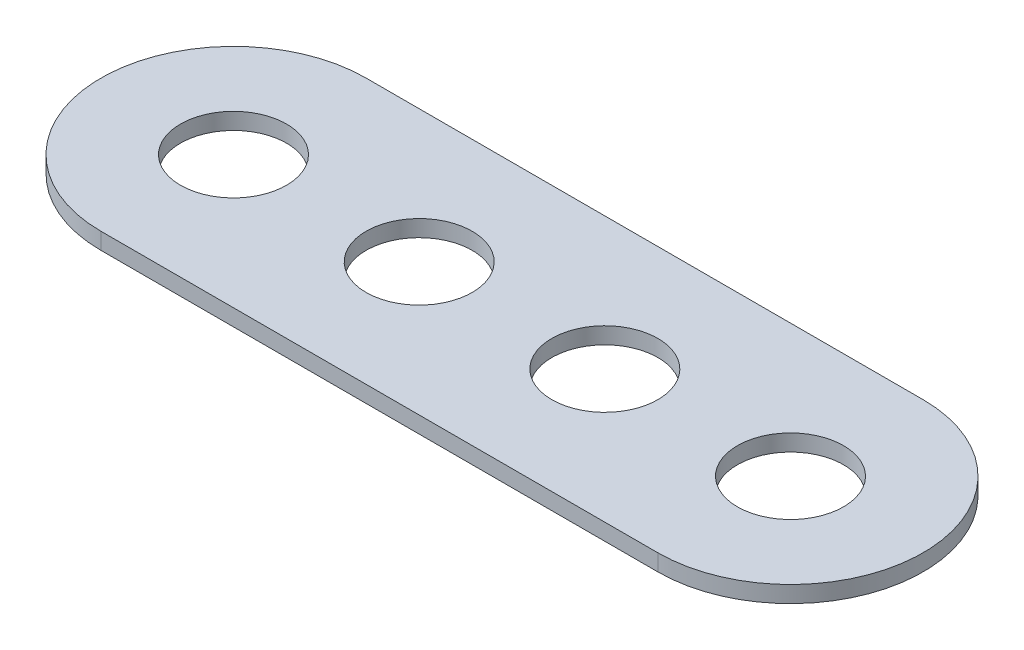
SolidWorks part; units mm, degrees
ref_plane "Front Plane" through (0, 0, 0) normal (0, 0, 1) x (1, 0, 0)
ref_plane "Top Plane" through (0, 0, 0) normal (0, 1, 0) x (1, 0, 0)
ref_plane "Right Plane" through (0, 0, 0) normal (1, 0, 0) x (0, 0, -1)
sketch "Sketch1" plane through (0, 0, 0) normal (0, 1, 0) x (1, 0, 0)
  line L0 (0, 0) -> (-106.68, 0) construction
  line L1 (0, 25.4) -> (-106.68, 25.4)
  line L2 (0, -25.4) -> (-106.68, -25.4)
  arc A0 (0, -25.4) -> (0, 25.4) centre (0, 0) ccw
  arc A1 (-106.68, 25.4) -> (-106.68, -25.4) centre (-106.68, 0) ccw
  dimension "D1" = 50.8
  dimension "D2" = 106.68
extrude "Boss-Extrude1" add sketch "Sketch1" along normal blind 3.175
sketch "Sketch3" plane through (0, 3.175, 0) normal (0, 1, 0) x (1, 0, 0)
  circle A1 centre (-106.68, 0) radius 10.16
  dimension "D1" = 20.32
extrude "Cut-Extrude1" cut sketch "Sketch3" against normal through all
pattern_linear "LPattern1" count 4 spacing 35.56 along (1, 0, 0) of "Cut-Extrude1"
